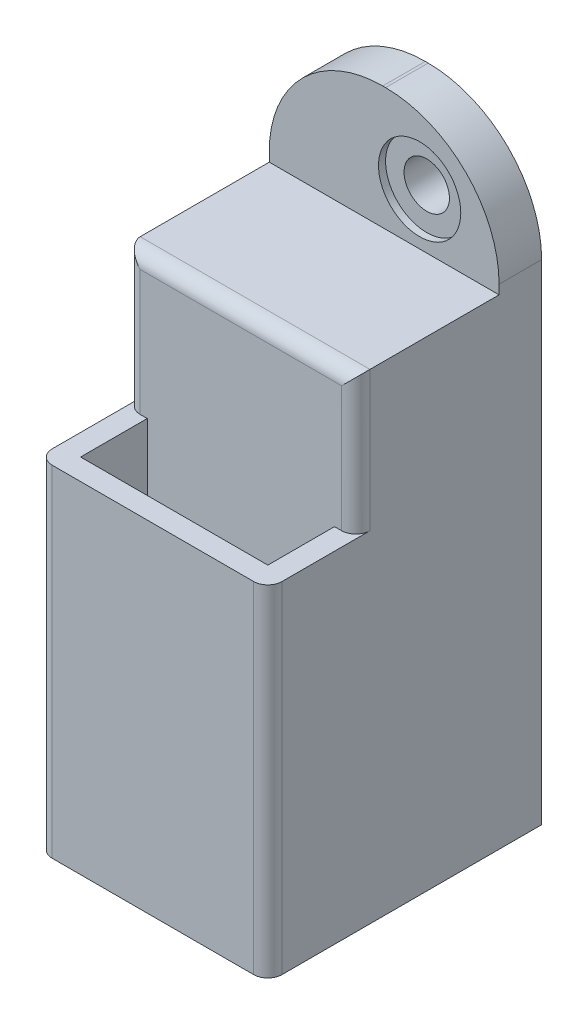
SolidWorks part; units mm, degrees
ref_plane "Alzado" through (0, 0, 0) normal (0, 0, 1) x (1, 0, 0)
ref_plane "Planta" through (0, 0, 0) normal (0, 1, 0) x (1, 0, 0)
ref_plane "Vista lateral" through (0, 0, 0) normal (1, 0, 0) x (0, 0, -1)
sketch "Croquis2" plane through (0, 0, 0) normal (0, 1, 0) x (1, 0, 0)
  line L0 (-1.5, 1.5) -> (14.7, 1.5)
  line L1 (0, 0) -> (13.2, 0)
  line L2 (0, 0) -> (0, -6.2)
  line L3 (0, -6.2) -> (13.2, -6.2)
  line L4 (13.2, 0) -> (13.2, -6.2)
  line L5 (14.7, 1.5) -> (14.7, -7.7)
  line L6 (-1.5, -7.7) -> (14.7, -7.7)
  line L7 (-1.5, 1.5) -> (-1.5, -7.7)
  dimension "D1" = 13.2
  dimension "D2" = 6.2
  dimension "D3" = 1.5
extrude "Saliente-Extruir1" add sketch "Croquis2" along normal blind 6.5
sketch "Croquis3" plane through (0, 0, -1.5) normal (0, 0, -1) x (-1, 0, 0)
  line L1 (1.5, 0) -> (-14.7, 0)
  line L2 (1.5, 0) -> (1.5, 12)
  line L3 (1.5, 12) -> (-14.7, 12)
  line L4 (-14.7, 0) -> (-14.7, 12)
  line L6 (-14.7, 0) -> (1.5, 0) construction
  line L8 (-14.7, 6.5) -> (-14.7, 0) construction
  line L9 (1.5, 6.5) -> (1.5, 0) construction
  dimension "D1" = 12
extrude "Saliente-Extruir2" add sketch "Croquis3" along normal blind 2
sketch "Croquis4" plane through (0, 0, -3.5) normal (0, 0, -1) x (-1, 0, 0)
  line L10 (1.5, 0) -> (1.5, 12) construction
  line L11 (1.5, 12) -> (-14.7, 12) construction
  line L12 (-14.7, 12) -> (-14.7, 0) construction
  line L13 (1.5, 0) -> (1.5, 12)
  line L14 (1.5, 12) -> (-14.7, 12)
  line L15 (-14.7, 12) -> (-14.7, 0)
  line L16 (-0.3, 0) -> (-0.3, 11)
  line L17 (-14.7, 0) -> (1.5, 0) construction
  line L18 (-0.3, 11) -> (-12.9, 11)
  line L19 (-12.9, 11) -> (-12.9, 0)
  line L20 (1.5, 0) -> (-0.3, 0)
  line L21 (-12.9, 0) -> (-14.7, 0)
  dimension "D1" = 1
  dimension "D2" = 1.8
  dimension "D3" = 1.8
extrude "Saliente-Extruir3" add sketch "Croquis4" along normal blind 8.1
sketch "Croquis5" plane through (0, 12, 0) normal (0, 1, 0) x (1, 0, 0)
  line L0 (-1.5, 11.6) -> (-1.5, 1.5) construction
  line L1 (14.7, 11.6) -> (-1.5, 11.6)
  line L2 (14.7, 11.6) -> (14.7, 8.6)
  line L3 (14.7, 8.6) -> (-1.5, 8.6)
  line L4 (-1.5, 11.6) -> (-1.5, 8.6)
  dimension "D1" = 3
extrude "Saliente-Extruir4" add sketch "Croquis5" along normal blind 13
sketch "Croquis6" plane through (0, 0, -8.6) normal (0, 0, 1) x (1, 0, 0)
  line L0 (14.7, 25) -> (14.7, 12) construction
  line L1 (-1.5, 25) -> (14.7, 25) construction
  circle A0 centre (9.1, 20) radius 1.6
  dimension "D1" = 3.2
  dimension "D2" = 5.6
  dimension "D3" = 5
extrude "Cortar-Extruir1" cut sketch "Croquis6" against normal up to surface (3 mm away) up to face at (6.6, 9, -11.6)
sketch "Croquis7" plane through (0, 0, -1.5) normal (0, 0, 1) x (1, 0, 0)
  line L0 (-1.5, 6.5) -> (-1.5, 12) construction
  line L1 (14.7, 6.5) -> (-1.5, 6.5)
  line L2 (14.7, 6.5) -> (14.7, 8.5)
  line L3 (14.7, 8.5) -> (-1.5, 8.5)
  line L4 (-1.5, 6.5) -> (-1.5, 8.5)
  dimension "D1" = 2
extrude "Saliente-Extruir5" add sketch "Croquis7" along normal blind 3
sketch "Croquis8" plane through (0, 0, -8.6) normal (0, 0, 1) x (1, 0, 0)
  circle A0 centre (9.1, 20) radius 2.9
  dimension "D1" = 5.8
extrude "Cortar-Extruir2" cut sketch "Croquis8" against normal blind 0.5
fillet "Redondeo1" radius 1 2 edges at (-1.5, 3.25, 7.7) (14.7, 3.25, 7.7)
fillet "Redondeo6" radius 8 2 edges at (14.7, 25, -10.1) (-1.5, 25, -10.1)
sketch "Croquis9" plane through (0, 0, 0) normal (0, -1, 0) x (1, 0, 0)
  line L0 (0, 0) -> (0, 6.2) construction
  line L1 (0, 6.2) -> (13.2, 6.2) construction
  line L2 (13.2, 6.2) -> (13.2, 0) construction
  line L3 (13.2, 0) -> (0, 0) construction
  line L4 (0, 0) -> (0, 6.2)
  line L5 (0, 6.2) -> (13.2, 6.2)
  line L6 (13.2, 6.2) -> (13.2, 0)
  line L7 (13.2, 0) -> (0, 0)
  line L8 (13.7, 7.7) -> (-0.5, 7.7)
  line L9 (-1.5, 6.7) -> (-1.5, -11.6)
  line L10 (-1.5, -11.6) -> (0.3, -11.6)
  line L11 (0.3, -11.6) -> (0.3, -3.5)
  line L12 (0.3, -3.5) -> (12.9, -3.5)
  line L13 (12.9, -3.5) -> (12.9, -11.6)
  line L14 (12.9, -11.6) -> (14.7, -11.6)
  line L15 (14.7, -11.6) -> (14.7, 6.7)
  line L16 (13.7, 7.7) -> (-0.5, 7.7)
  line L17 (-1.5, 6.7) -> (-1.5, -11.6)
  line L18 (-1.5, -11.6) -> (0.3, -11.6)
  line L19 (0.3, -11.6) -> (0.3, -3.5)
  line L20 (0.3, -3.5) -> (12.9, -3.5)
  line L21 (12.9, -3.5) -> (12.9, -11.6)
  line L22 (12.9, -11.6) -> (14.7, -11.6)
  line L23 (14.7, -11.6) -> (14.7, 6.7)
  arc A2 (-0.5, 7.7) -> (-1.5, 6.7) centre (-0.5, 6.7) ccw
  arc A3 (14.7, 6.7) -> (13.7, 7.7) centre (13.7, 6.7) ccw
  arc A4 (-0.5, 7.7) -> (-1.5, 6.7) centre (-0.5, 6.7) ccw
  arc A5 (14.7, 6.7) -> (13.7, 7.7) centre (13.7, 6.7) ccw
  dimension "D1" = 0
extrude "Saliente-Extruir6" add sketch "Croquis9" along normal blind 3.5
sketch "Croquis10" plane through (0, 6.5, 0) normal (0, -1, 0) x (1, 0, 0)
  line L4 (0, 1.5) -> (0, 0)
  line L5 (0, 0) -> (13.2, 0)
  line L6 (13.2, 0) -> (13.2, 1.5)
  line L7 (13.2, 1.5) -> (0, 1.5)
  line L8 (0, 1.5) -> (0, 0)
  line L9 (0, 0) -> (13.2, 0)
  line L10 (13.2, 0) -> (13.2, 1.5)
  line L11 (13.2, 1.5) -> (0, 1.5)
  dimension "D1" = 0
extrude "Saliente-Extruir7" add sketch "Croquis10" along normal blind 3.5
sketch "Croquis11" plane through (0, -3.5, 0) normal (0, -1, 0) x (1, 0, 0)
  line L0 (0, 6.2) -> (0, 0) construction
  line L1 (13.2, 6.2) -> (0, 6.2) construction
  line L2 (13.2, 0) -> (13.2, 6.2) construction
  line L3 (0, 0) -> (13.2, 0) construction
  line L4 (0, 6.2) -> (0, 0)
  line L5 (13.2, 6.2) -> (0, 6.2)
  line L6 (13.2, 0) -> (13.2, 6.2)
  line L7 (0, 0) -> (13.2, 0)
  line L8 (13.7, 7.7) -> (-0.5, 7.7)
  line L9 (-1.5, 6.7) -> (-1.5, -11.6)
  line L10 (-1.5, -11.6) -> (0.3, -11.6)
  line L11 (0.3, -11.6) -> (0.3, -3.5)
  line L12 (0.3, -3.5) -> (12.9, -3.5)
  line L13 (12.9, -3.5) -> (12.9, -11.6)
  line L14 (12.9, -11.6) -> (14.7, -11.6)
  line L15 (14.7, -11.6) -> (14.7, 6.7)
  line L16 (13.7, 7.7) -> (-0.5, 7.7)
  line L17 (-1.5, 6.7) -> (-1.5, -11.6)
  line L18 (-1.5, -11.6) -> (0.3, -11.6)
  line L19 (0.3, -11.6) -> (0.3, -3.5)
  line L20 (0.3, -3.5) -> (12.9, -3.5)
  line L21 (12.9, -3.5) -> (12.9, -11.6)
  line L22 (12.9, -11.6) -> (14.7, -11.6)
  line L23 (14.7, -11.6) -> (14.7, 6.7)
  arc A2 (14.7, 6.7) -> (13.7, 7.7) centre (13.7, 6.7) ccw
  arc A3 (-0.5, 7.7) -> (-1.5, 6.7) centre (-0.5, 6.7) ccw
  arc A4 (14.7, 6.7) -> (13.7, 7.7) centre (13.7, 6.7) ccw
  arc A5 (-0.5, 7.7) -> (-1.5, 6.7) centre (-0.5, 6.7) ccw
  dimension "D1" = 0
extrude "Saliente-Extruir8" add sketch "Croquis11" along normal blind 14
sketch "Croquis12" plane through (0, 3, 0) normal (0, -1, 0) x (1, 0, 0)
  line L4 (13.2, 1.5) -> (0, 1.5)
  line L5 (0, 1.5) -> (0, 0)
  line L6 (0, 0) -> (13.2, 0)
  line L7 (13.2, 0) -> (13.2, 1.5)
  line L8 (13.2, 1.5) -> (0, 1.5)
  line L9 (0, 1.5) -> (0, 0)
  line L10 (0, 0) -> (13.2, 0)
  line L11 (13.2, 0) -> (13.2, 1.5)
  dimension "D1" = 0
extrude "Saliente-Extruir9" add sketch "Croquis12" along normal blind 14
sketch "Croquis13" plane through (0, 0, -8.6) normal (0, 0, 1) x (1, 0, 0)
  line L0 (14.7, 17) -> (14.7, 12) construction
  line L1 (14.7, 16.35) -> (-1.5, 16.35)
  line L2 (14.7, 16.35) -> (14.7, 8.5)
  line L3 (14.7, 8.5) -> (-1.5, 8.5)
  line L4 (-1.5, 16.35) -> (-1.5, 8.5)
  line L5 (-1.5, 17) -> (-1.5, 12) construction
  line L6 (14.7, 8.5) -> (-1.5, 8.5) construction
  line L7 (14.7, 8.5) -> (-1.5, 8.5) construction
  line L8 (-1.5, 12) -> (14.7, 12) construction
  dimension "D1" = 4.35
extrude "Saliente-Extruir10" add sketch "Croquis13" along normal up to surface (10.1 mm away) up to face at (6.6, 2.625, 1.5)
sketch "Croquis14" plane through (0, 0, -11.6) normal (0, 0, -1) x (-1, 0, 0)
  line L0 (-0.3, 11) -> (-0.3, 8.5) construction
  line L1 (-12.9, 8.5) -> (-0.3, 8.5)
  line L2 (-12.9, 8.5) -> (-12.9, 15)
  line L3 (-12.9, 15) -> (-0.3, 15)
  line L4 (-0.3, 8.5) -> (-0.3, 15)
  dimension "D1" = 6.5
extrude "Cortar-Extruir3" cut sketch "Croquis14" against normal up to surface (8.1 mm away) up to face at (6.6, -4.5, -3.5)
fillet "Redondeo7" radius 1 3 edges at (6.6, 16.35, 1.5) (-1.5, 11.425, 1.5) (14.7, 11.425, 1.5)
